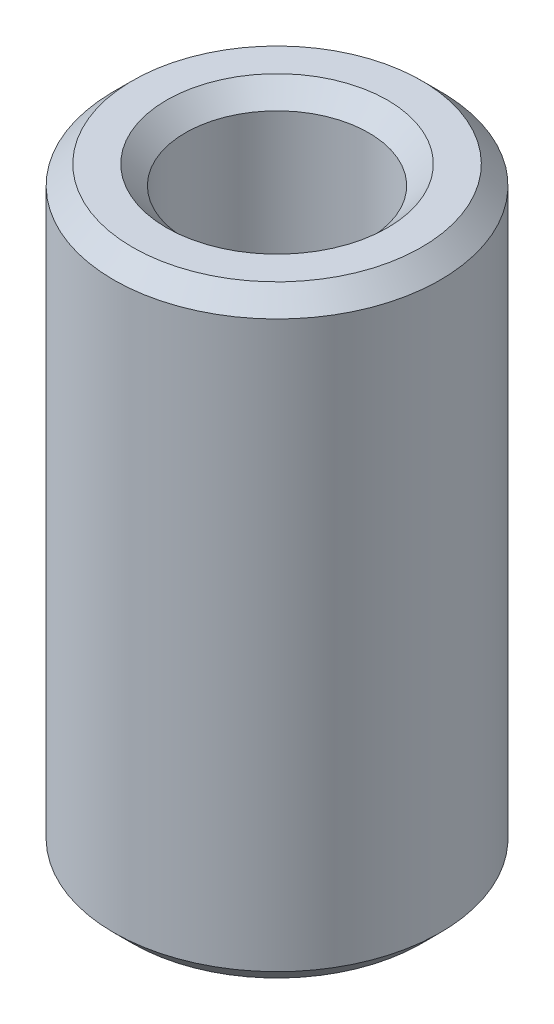
SolidWorks part; units mm, degrees
material "ABS"
ref_plane "Alzado" through (0, 0, 0) normal (0, 0, 1) x (1, 0, 0)
ref_plane "Planta" through (0, 0, 0) normal (0, 1, 0) x (1, 0, 0)
ref_plane "Vista lateral" through (0, 0, 0) normal (1, 0, 0) x (0, 0, -1)
sketch "Croquis1" plane through (0, 0, 0) normal (0, 1, 0) x (1, 0, 0)
  circle A0 centre (0, 0) radius 3.65
  circle A1 centre (0, 0) radius 6.5
  dimension "D1" = 7.3
  dimension "D2" = 13
extrude "Saliente-Extruir1" add sketch "Croquis1" along normal mid plane 24
chamfer "Chaflán1" distance 0.75 angle 45 4 edges at (0, 12, 3.65) (0, -12, 3.65) (0, -12, 6.5) (0, 12, 6.5)
